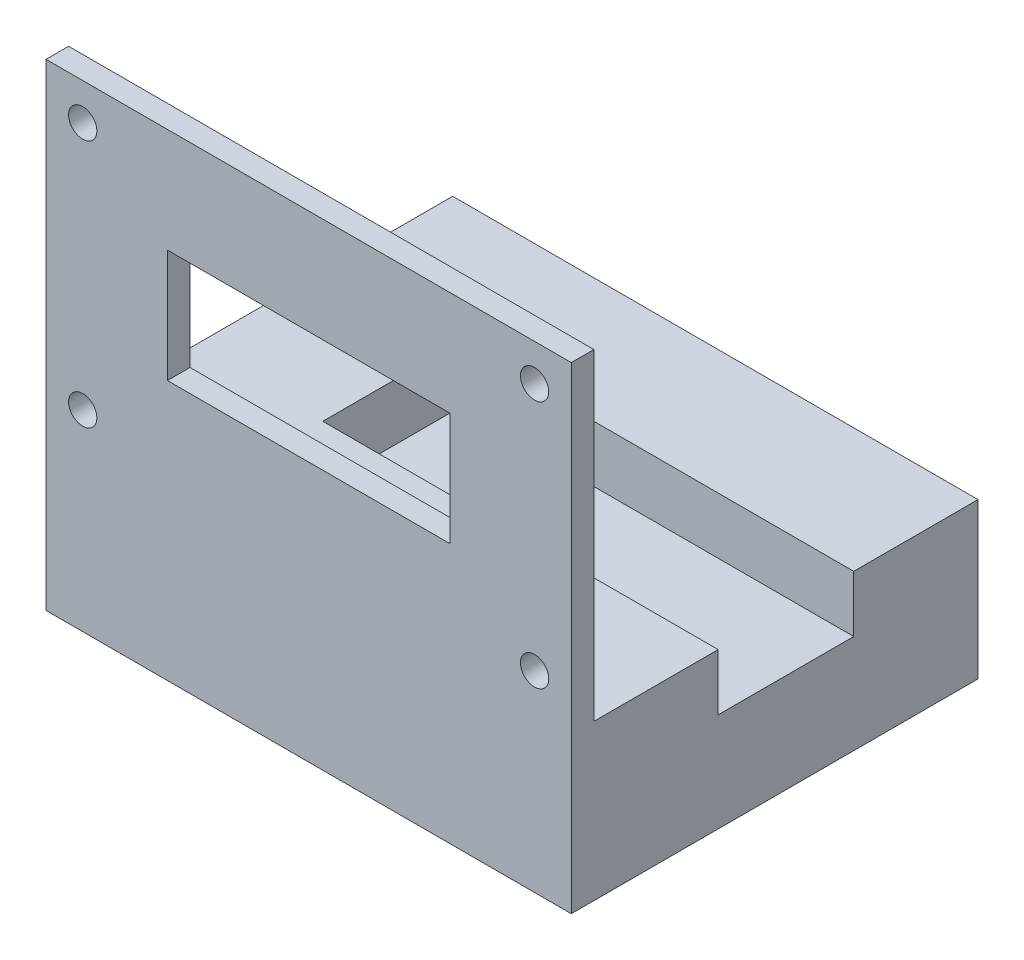
SolidWorks part; units mm, degrees
ref_plane "Front Plane" through (0, 0, 0) normal (0, 0, 1) x (1, 0, 0)
ref_plane "Top Plane" through (0, 0, 0) normal (0, 1, 0) x (1, 0, 0)
ref_plane "Right Plane" through (0, 0, 0) normal (1, 0, 0) x (0, 0, -1)
sketch "Sketch1" plane through (0, 0, 0) normal (0, 1, 0) x (1, 0, 0)
  line L1 (-23.25, -17) -> (23.25, -17)
  line L2 (-23.25, -17) -> (-23.25, 17)
  line L3 (-23.25, 17) -> (23.25, 17)
  line L4 (23.25, -17) -> (23.25, 17)
  line L5 (-23.25, -17) -> (23.25, 17) construction
  line L6 (-23.25, 17) -> (23.25, -17) construction
  point P0 (0, 0)
  dimension "D1" = 46.5
  dimension "D2" = 34
extrude "Boss-Extrude1" add sketch "Sketch1" along normal blind 13.75
sketch "Sketch2" plane through (0, 0, 17) normal (0, 0, 1) x (1, 0, 0)
  line L1 (-23.25, 0) -> (23.25, 0)
  line L2 (-23.25, 0) -> (-23.25, 42.25)
  line L3 (-23.25, 42.25) -> (23.25, 42.25)
  line L4 (23.25, 0) -> (23.25, 42.25)
  dimension "D1" = 46.5
  dimension "D2" = 42.25
extrude "Boss-Extrude2" add sketch "Sketch2" along normal blind 2
sketch "Sketch3" plane through (0, 0, 19) normal (0, 0, 1) x (1, 0, 0)
  line L0 (-23.25, 28) -> (23.25, 28) construction
  line L1 (-12.5, 33) -> (12.5, 33)
  line L2 (-12.5, 33) -> (-12.5, 23)
  line L3 (-12.5, 23) -> (12.5, 23)
  line L4 (12.5, 33) -> (12.5, 23)
  line L5 (23.25, 0) -> (23.25, 42.25) construction
  line L6 (23.25, 42.25) -> (-23.25, 42.25) construction
  line L7 (-23.25, 42.25) -> (-23.25, 0) construction
  circle A0 centre (-20, 39) radius 1.25
  circle A2 centre (20, 39) radius 1.25
  circle A4 centre (20, 17) radius 1.25
  circle A5 centre (-20, 17) radius 1.25
  dimension "D1" = 2.5
  dimension "D11" = 2.5
  dimension "D2" = 10
  dimension "D3" = 25
  dimension "D4" = 5
  dimension "D5" = 10.75
  dimension "D6" = 14.25
  dimension "D7" = 3.25
  dimension "D8" = 3.25
  dimension "D9" = 3.25
  dimension "D10" = 3.25
extrude "Cut-Extrude1" cut sketch "Sketch3" against normal up to next
sketch "Sketch4" plane through (0, 13.75, 0) normal (0, 1, 0) x (1, 0, 0)
  line L0 (23.25, -17) -> (23.25, 17) construction
  line L1 (23.25, 6) -> (-11.75, 6)
  line L2 (23.25, 6) -> (23.25, -6)
  line L3 (23.25, -6) -> (-11.75, -6)
  line L4 (-11.75, 6) -> (-11.75, -6)
  line L5 (23.25, 17) -> (-23.25, 17) construction
  dimension "D1" = 35
  dimension "D2" = 12
  dimension "D3" = 11
extrude "Cut-Extrude2" cut sketch "Sketch4" against normal blind 5
sketch "Sketch6" plane through (0, 0, 0) normal (0, -1, 0) x (1, 0, 0)
  line L0 (16.25, -10) -> (16.25, 12)
  line L1 (23.25, -17) -> (-23.25, -17)
  line L2 (23.25, -17) -> (23.25, 19)
  line L3 (23.25, 19) -> (-23.25, 19)
  line L4 (-23.25, -17) -> (-23.25, 19)
  line L5 (16.25, 12) -> (-16.25, 12)
  line L6 (-16.25, -10) -> (-16.25, 12)
  line L7 (16.25, -10) -> (-16.25, -10)
  circle A0 centre (16.25, -10) radius 2
  circle A1 centre (16.25, 12) radius 2
  circle A2 centre (-16.25, -10) radius 2
  circle A3 centre (-16.25, 12) radius 2
  dimension "D2" = 4
  dimension "D3" = 4
  dimension "D4" = 4
  dimension "D5" = 4
  dimension "D1" = 7
extrude "Cut-Extrude3" cut sketch "Sketch6" against normal blind 10 contours A0 | A1 | A2 | A3
